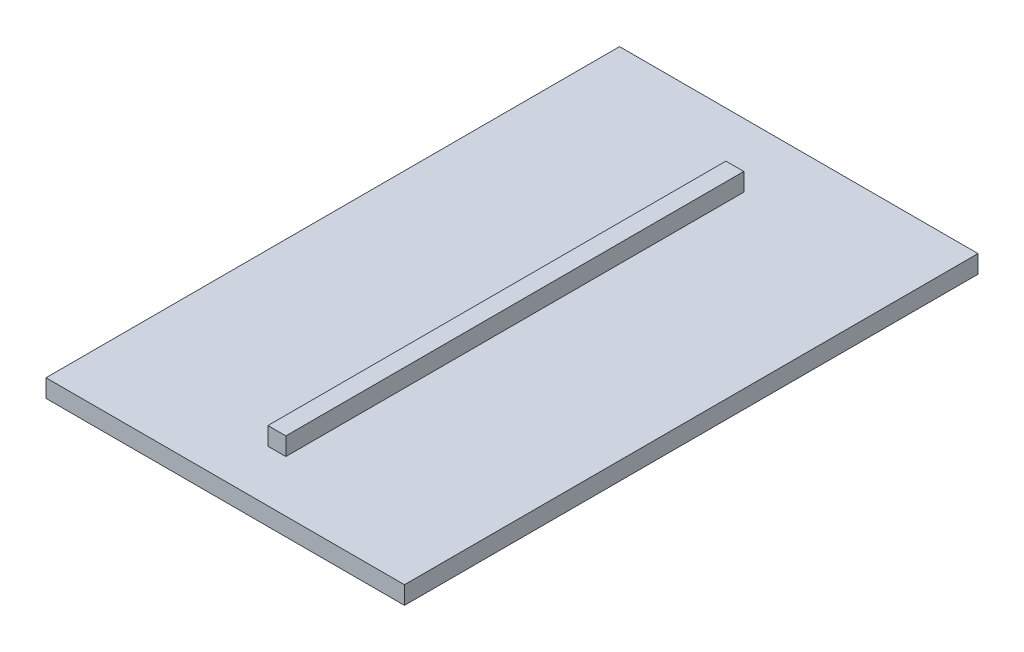
SolidWorks part; units mm, degrees
ref_plane "Front Plane" through (0, 0, 0) normal (0, 0, 1) x (1, 0, 0)
ref_plane "Top Plane" through (0, 0, 0) normal (0, 1, 0) x (1, 0, 0)
ref_plane "Right Plane" through (0, 0, 0) normal (1, 0, 0) x (0, 0, -1)
sketch "Sketch1" plane through (0, 0, 0) normal (0, 1, 0) x (1, 0, 0)
  line L1 (-5, 8) -> (5, 8)
  line L2 (-5, 8) -> (-5, -8)
  line L3 (-5, -8) -> (5, -8)
  line L4 (5, 8) -> (5, -8)
  line L5 (-5, 8) -> (5, -8) construction
  line L6 (-5, -8) -> (5, 8) construction
  point P0 (0, 0)
  dimension "D1" = 10
  dimension "D2" = 16
extrude "Boss-Extrude1" add sketch "Sketch1" along normal blind 0.5
sketch "Sketch3" plane through (0, 0.5, 0) normal (0, 1, 0) x (1, 0, 0)
  line L1 (-0.25, 6.2173) -> (0.25, 6.2173)
  line L2 (-0.25, 6.2173) -> (-0.25, -6.5591)
  line L3 (-0.25, -6.5591) -> (0.25, -6.5591)
  line L4 (0.25, 6.2173) -> (0.25, -6.5591)
  line L5 (-0.25, 6.2173) -> (0.25, -6.5591) construction
  line L6 (-0.25, -6.5591) -> (0.25, 6.2173) construction
  point P0 (0, -0.1709)
  point P5 (0.4972, 6.3664)
  point P6 (-0.4908, -0.0481)
  point P7 (-0.8471, -0.0656)
  point P8 (-0.192, -0.1498)
  point P9 (0, -0.1709)
  dimension "D1" = 0.5
extrude "Boss-Extrude2" add sketch "Sketch3" along normal blind 0.5
